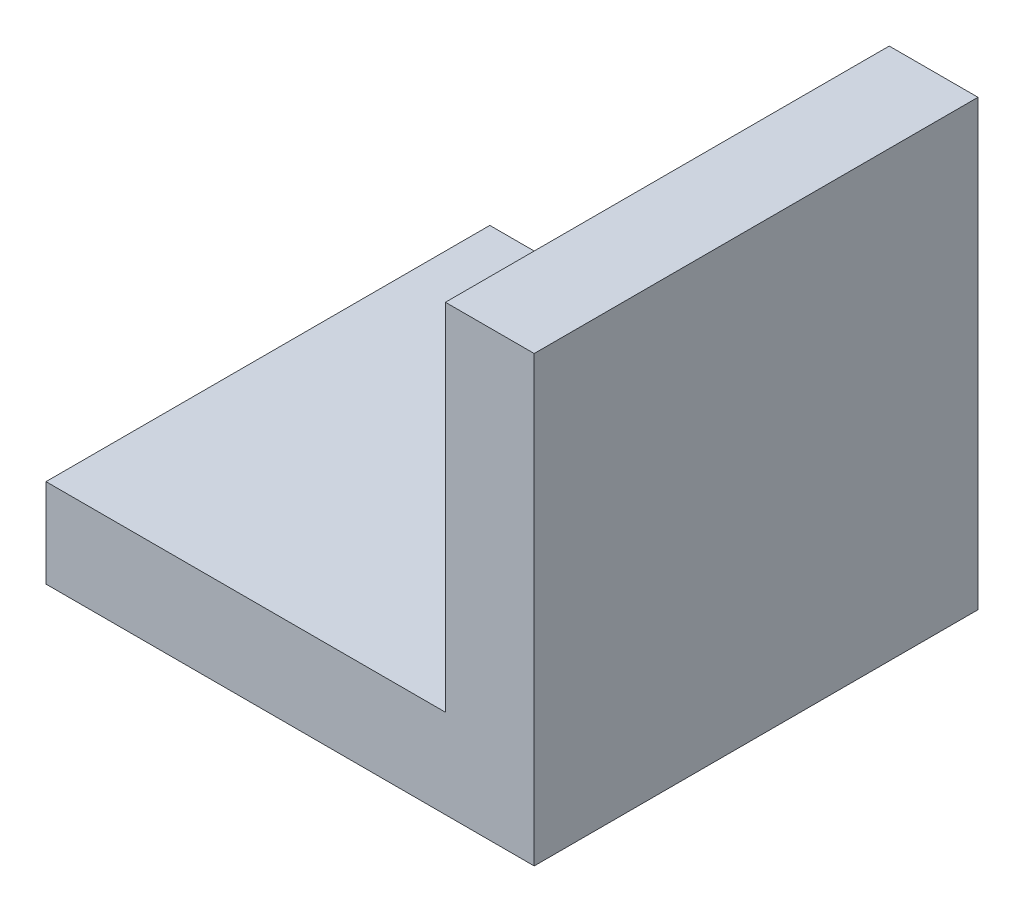
SolidWorks part; units mm, degrees
ref_plane "Plan de face" through (0, 0, 0) normal (0, 0, 1) x (1, 0, 0)
ref_plane "Plan de dessus" through (0, 0, 0) normal (0, 1, 0) x (1, 0, 0)
ref_plane "Plan de droite" through (0, 0, 0) normal (1, 0, 0) x (0, 0, -1)
sketch "Esquisse1" plane through (0, 0, 0) normal (0, 0, 1) x (1, 0, 0)
  line L0 (0, 0) -> (-55, 0)
  line L1 (-55, 0) -> (-55, 10)
  line L2 (-55, 10) -> (-10, 10)
  line L3 (-10, 10) -> (-10, 50)
  line L4 (-10, 50) -> (0, 50)
  line L5 (0, 50) -> (0, 0)
  dimension "D1" = 55
  dimension "D2" = 10
  dimension "D3" = 40
  dimension "D4" = 10
extrude "Boss.-Extru.1" add sketch "Esquisse1" along normal blind 50
